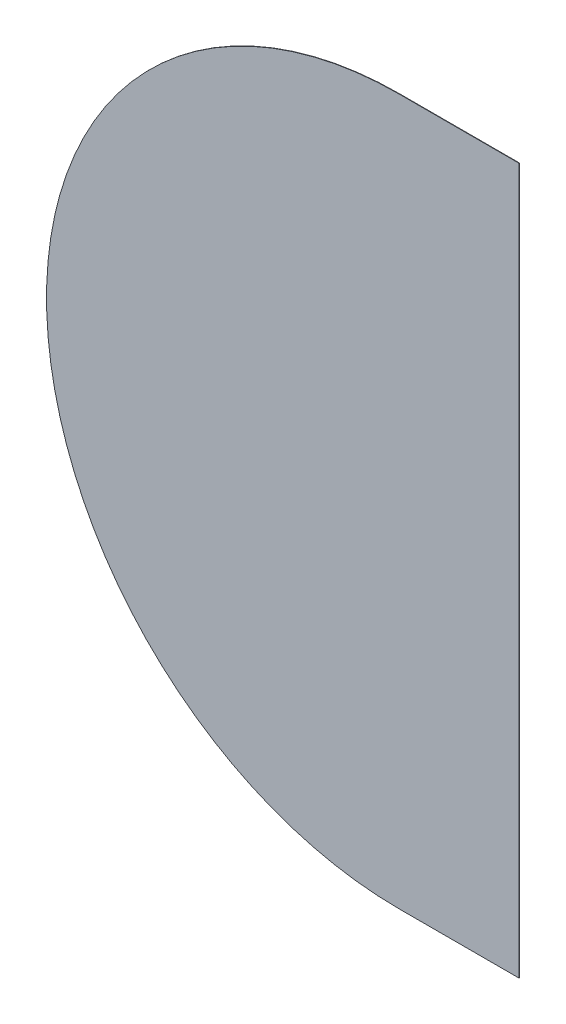
SolidWorks part; units mm, degrees
ref_plane "Front Plane" through (0, 0, 0) normal (0, 0, 1) x (1, 0, 0)
ref_plane "Top Plane" through (0, 0, 0) normal (0, 1, 0) x (1, 0, 0)
ref_plane "Right Plane" through (0, 0, 0) normal (1, 0, 0) x (0, 0, -1)
sketch "Sketch1" plane through (0, 0, 0) normal (0, 0, 1) x (1, 0, 0)
  line L1 (0, 0) -> (270, 0)
  line L2 (0, 0) -> (0, 1595) construction
  line L3 (0, 1595) -> (270, 1595)
  line L4 (270, 0) -> (270, 1595)
  arc A0 (0, 1595) -> (0, 0) centre (0, 797.5) ccw
  dimension "D1" = 270
  dimension "D2" = 1595
extrude "Boss-Extrude1" add sketch "Sketch1" along normal blind 1
